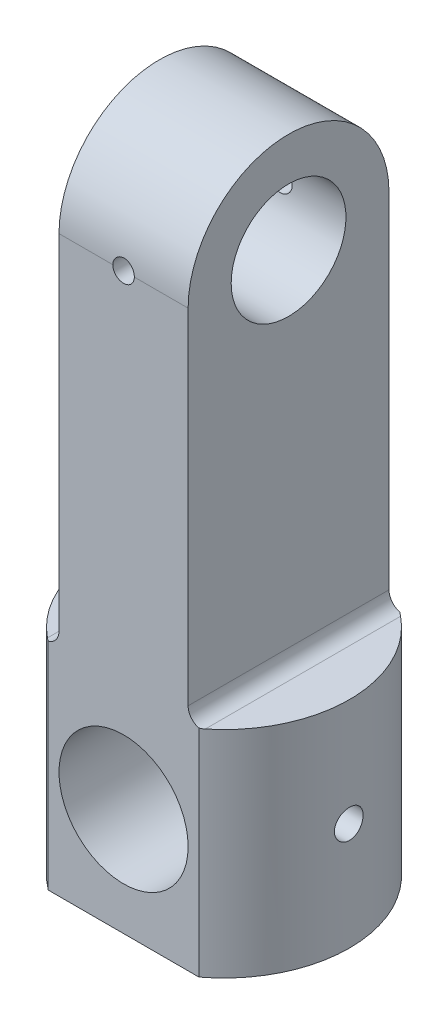
SolidWorks part; units mm, degrees
material "Plain Carbon Steel"
ref_plane "Front Plane" through (0, 0, 0) normal (0, 0, 1) x (1, 0, 0)
ref_plane "Top Plane" through (0, 0, 0) normal (0, 1, 0) x (1, 0, 0)
ref_plane "Right Plane" through (0, 0, 0) normal (1, 0, 0) x (0, 0, -1)
sketch "Sketch1" plane through (0, 0, 0) normal (0, 1, 0) x (1, 0, 0)
  circle A0 centre (0, 0) radius 17.5
  dimension "D1" = 35
extrude "Boss-Extrude1" add sketch "Sketch1" along normal blind 30
sketch "Sketch2" plane through (0, 30, 0) normal (0, 1, 0) x (1, 0, 0)
  line L1 (-9, -15.0083) -> (9, -15.0083)
  line L2 (-9, -15.0083) -> (-9, 15.0083)
  line L3 (-9, 15.0083) -> (9, 15.0083)
  line L4 (9, -15.0083) -> (9, 15.0083)
  line L5 (-9, -15.0083) -> (9, 15.0083) construction
  line L6 (-9, 15.0083) -> (9, -15.0083) construction
  circle A0 centre (0, 0) radius 17.5 construction
  point P0 (0, 0)
  dimension "D1" = 18
extrude "Boss-Extrude2" add sketch "Sketch2" along normal blind 70
sketch "Sketch3" plane through (0, 0, 0) normal (0, -1, 0) x (1, 0, 0)
  line L1 (-10.5, -14) -> (10.5, -14)
  line L3 (-10.5, 14) -> (10.5, 14)
  circle A0 centre (0, 0) radius 17.5 construction
  arc A1 (-10.5, -14) -> (10.5, -14) centre (0, 0) ccw
  arc A2 (10.5, 14) -> (-10.5, 14) centre (0, 0) ccw
  point P0 (0, 0)
  dimension "D1" = 28
extrude "Cut-Extrude1" cut sketch "Sketch3" against normal through all both and the other way through all
sketch "Sketch4" plane through (-9, 0, 0) normal (-1, 0, 0) x (0, 0, 1)
  line L0 (55, 0) -> (-55, 0) construction
  line L1 (-14, 80) -> (-32.8665, 80)
  line L2 (-32.8665, 80) -> (-32.8665, 110.1162)
  line L3 (-32.8665, 110.1162) -> (25.9047, 110.1162)
  line L4 (25.9047, 110.1162) -> (25.9047, 80)
  line L5 (25.9047, 80) -> (14, 80)
  line L9 (-14, 100) -> (-14, 30) construction
  line L10 (14, 30) -> (14, 100) construction
  circle A0 centre (0, 80) radius 8
  arc A1 (14, 80) -> (-14, 80) centre (0, 80) ccw
  dimension "D1" = 80
  dimension "D2" = 16
extrude "Cut-Extrude2" cut sketch "Sketch4" against normal through all both and the other way through all
sketch "Sketch6" plane through (0, 0, -14) normal (0, 0, 1) x (1, 0, 0)
  line L0 (0, -44.7868) -> (0, 44.7868) construction
  line L1 (55, 0) -> (-55, 0) construction
  circle A4 centre (0, 15) radius 9
  dimension "D1" = 18
  dimension "D2" = 15
extrude "Cut-Extrude3" cut sketch "Sketch6" against normal through all both and the other way through all
fillet "Fillet1" radius 2 2 edges at (9, 30, 0) (-9, 30, 0)
sketch "Sketch7" plane through (0, 0, 0) normal (1, 0, 0) x (0, 0, -1)
  line L0 (0, 44.2539) -> (0, -44.2539) construction
  line L1 (55, 0) -> (-55, 0) construction
  circle A0 centre (0, 15) radius 2
  dimension "D1" = 4
  dimension "D2" = 15
extrude "Cut-Extrude4" cut sketch "Sketch7" against normal through all both and the other way through all
sketch "Sketch8" plane through (0, 0, 0) normal (0, 0, 1) x (1, 0, 0)
  line L0 (55, 0) -> (-55, 0) construction
  line L1 (0, -44.7868) -> (0, 44.7868) construction
  circle A0 centre (0, 80) radius 1.5
  dimension "D1" = 3
  dimension "D2" = 80
extrude "Cut-Extrude5" cut sketch "Sketch8" against normal through all both and the other way through all
